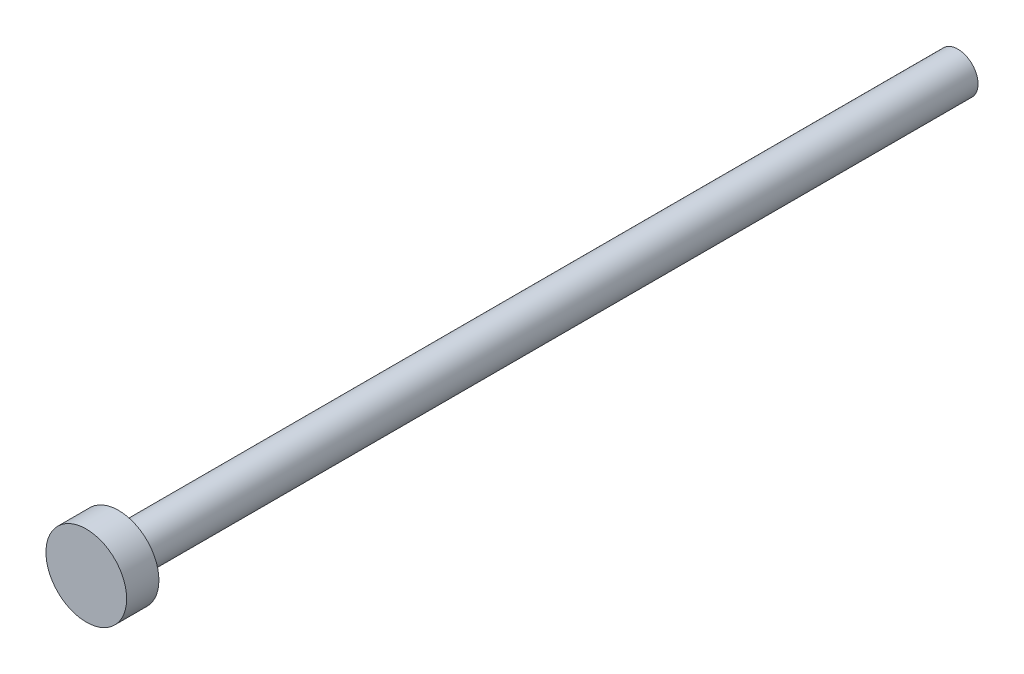
SolidWorks part; units mm, degrees
ref_plane "Front Plane" through (0, 0, 0) normal (0, 0, 1) x (1, 0, 0)
ref_plane "Top Plane" through (0, 0, 0) normal (0, 1, 0) x (1, 0, 0)
ref_plane "Right Plane" through (0, 0, 0) normal (1, 0, 0) x (0, 0, -1)
sketch "Sketch1" plane through (0, 0, 0) normal (0, 0, 1) x (1, 0, 0)
  circle A0 centre (0, 0) radius 1.25
  dimension "D1" = 2.5
extrude "Boss-Extrude1" add sketch "Sketch1" along normal blind 1
sketch "Sketch2" plane through (0, 0, 0) normal (0, 0, -1) x (-1, 0, 0)
  circle A0 centre (0, 0) radius 0.625
  dimension "D1" = 1.25
extrude "Boss-Extrude2" add sketch "Sketch2" along normal blind 26
